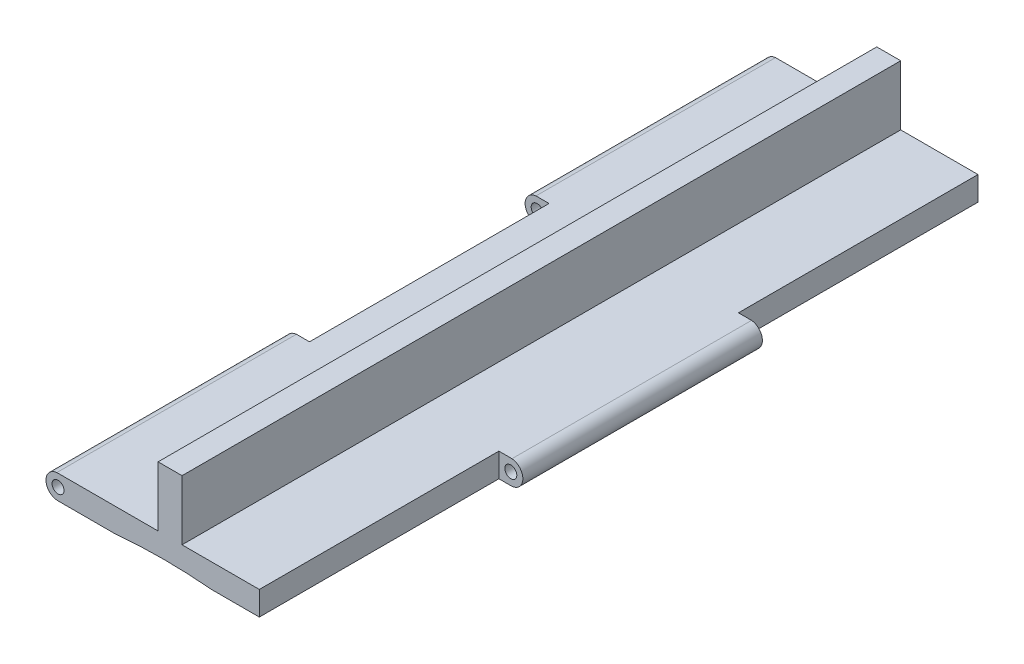
SolidWorks part; units mm, degrees
ref_plane "Front Plane" through (0, 0, 0) normal (0, 0, 1) x (1, 0, 0)
ref_plane "Top Plane" through (0, 0, 0) normal (0, 1, 0) x (1, 0, 0)
ref_plane "Right Plane" through (0, 0, 0) normal (1, 0, 0) x (0, 0, -1)
sketch "Sketch1" plane through (0, 0, 0) normal (0, 0, 1) x (1, 0, 0)
  line L1 (-6.4865, 2) -> (13.5135, 2)
  line L2 (-6.4865, 2) -> (-6.4865, 0)
  line L3 (-6.4865, 0) -> (13.5135, 0)
  line L4 (13.5135, 2) -> (13.5135, 0)
  dimension "D1" = 20
  dimension "D2" = 2
extrude "Boss-Extrude1" add sketch "Sketch1" along normal blind 60
sketch "Sketch4" plane through (0, 0, 0) normal (0, 0, -1) x (-1, 0, 0)
  line L1 (-13.5135, 2) -> (-12.5135, 2)
  line L2 (-13.5135, 2) -> (-13.5135, -0.005)
  line L3 (-13.5135, -0.005) -> (-12.4135, -0.005)
  line L5 (6.4865, 2) -> (5.4865, 2)
  line L6 (6.4865, 2) -> (6.4865, -0.005)
  line L7 (6.4865, -0.005) -> (5.3865, -0.005)
  arc A0 (-12.5135, 2) -> (-12.4135, -0.005) centre (-12.4135, 1) ccw
  arc A1 (5.4865, 2) -> (5.3865, -0.005) centre (5.3865, 1) cw
  dimension "D1" = 1.1
  dimension "D2" = 1.1
extrude "Cut-Extrude2" cut sketch "Sketch4" against normal blind 70
sketch "Sketch5" plane through (0, 0, 0) normal (0, 0, -1) x (-1, 0, 0)
  circle A0 centre (-12.4135, 1) radius 0.5
  circle A1 centre (5.3865, 1) radius 0.5
extrude "Cut-Extrude3" cut sketch "Sketch5" against normal blind 70
sketch "Sketch6" plane through (0, 2, 0) normal (0, 1, 0) x (1, 0, 0)
  line L0 (-6.3915, 0) -> (-6.3915, -60) construction
  line L1 (-6.3915, -20) -> (-4.3915, -20)
  line L2 (-6.3915, -20) -> (-6.3915, -40)
  line L3 (-6.3915, -40) -> (-4.3915, -40)
  line L4 (-4.3915, -20) -> (-4.3915, -40)
  line L5 (12.5135, 0) -> (-5.4865, 0) construction
  line L6 (11.4185, 0) -> (13.4185, 0)
  line L7 (11.4185, 0) -> (11.4185, -20)
  line L8 (11.4185, -20) -> (13.4185, -20)
  line L9 (13.4185, 0) -> (13.4185, -20)
  line L10 (13.4185, -60) -> (13.4185, 0) construction
  line L11 (12.5135, -60) -> (-5.4865, -60) construction
  line L12 (11.4185, -60) -> (13.4185, -60)
  line L13 (11.4185, -60) -> (11.4185, -40)
  line L14 (11.4185, -40) -> (13.4185, -40)
  line L15 (13.4185, -60) -> (13.4185, -40)
  dimension "D1" = 20
  dimension "D2" = 20
  dimension "D3" = 20
  dimension "D4" = 2
  dimension "D5" = 2
  dimension "D6" = 2
extrude "Cut-Extrude4" cut sketch "Sketch6" against normal blind 70
sketch "Sketch7" plane through (0, 0, 0) normal (0, 0, -1) x (-1, 0, 0)
  line L5 (-11.4185, 2) -> (5.4865, 2) construction
  line L6 (-4.966, 7) -> (-2.966, 7)
  line L7 (-4.966, 7) -> (-4.966, 2)
  line L8 (-4.966, 2) -> (-2.966, 2)
  line L9 (-2.966, 7) -> (-2.966, 2)
  dimension "D1" = 5
  dimension "D2" = 2
extrude "Boss-Extrude2" add sketch "Sketch7" against normal blind 60
sketch "Sketch9" plane through (0, 0, 0) normal (0, -1, 0) x (-1, 0, 0)
  line L0 (5.4865, -60) -> (-11.4185, -60) construction
  line L1 (0.5815, -60) -> (-7.4185, -60)
  line L2 (0.5815, -60) -> (0.5815, 0)
  line L3 (0.5815, 0) -> (-7.4185, 0)
  line L4 (-7.4185, -60) -> (-7.4185, 0)
  line L5 (5.4865, 0) -> (-11.4185, 0) construction
  line L6 (-11.4185, 0) -> (-11.4185, -20) construction
  dimension "D1" = 8
  dimension "D2" = 4
extrude "Cut-Extrude5" cut sketch "Sketch9" against normal blind 1
sketch "Sketch12" plane through (0, 0, 0) normal (0, 0, -1) x (-1, 0, 0)
  line L11 (-7.4185, 1) -> (0.5815, 1)
  line L12 (0.5815, 1) -> (0.5815, 0)
  line L13 (0.5815, 0) -> (5.4865, 0)
  line L14 (5.4865, 2) -> (-2.966, 2)
  line L15 (-2.966, 2) -> (-2.966, 7)
  line L16 (-2.966, 7) -> (-4.966, 7)
  line L17 (-4.966, 7) -> (-4.966, 2)
  line L18 (-4.966, 2) -> (-11.4185, 2)
  line L19 (-11.4185, 2) -> (-11.4185, 0)
  line L20 (-11.4185, 0) -> (-7.4185, 0)
  line L21 (-7.4185, 0) -> (-7.4185, 1)
  line L22 (-7.4185, 1) -> (0.5815, 1)
  line L23 (0.5815, 1) -> (0.5815, 0)
  line L32 (-7.4185, 0) -> (-7.4185, 1)
  arc A0 (-7.4185, 0) -> (0.5815, 0) centre (-3.4185, -42.3113) cw
  arc A2 (5.4865, 0) -> (5.4865, 2) centre (5.3865, 1) ccw
  dimension "D1" = 0
extrude "Boss-Extrude3" add sketch "Sketch12" against normal blind 60
